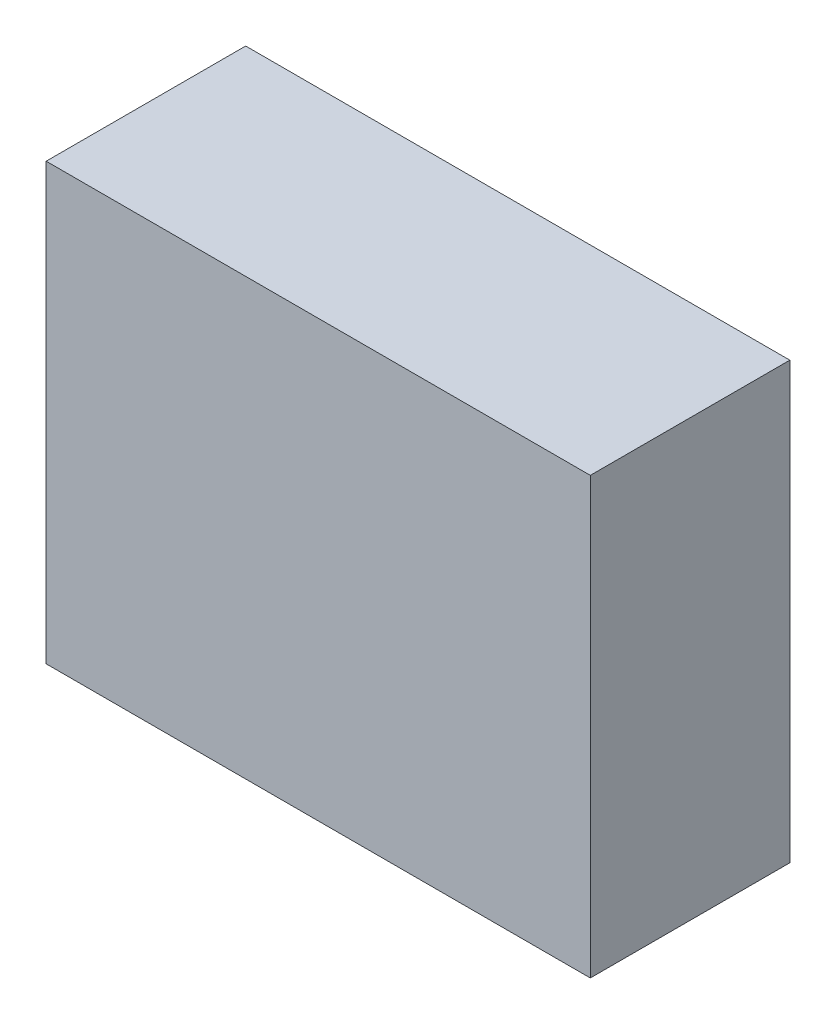
SolidWorks part; units mm, degrees
ref_plane "Front Plane" through (0, 0, 0) normal (0, 0, 1) x (1, 0, 0)
ref_plane "Top Plane" through (0, 0, 0) normal (0, 1, 0) x (1, 0, 0)
ref_plane "Right Plane" through (0, 0, 0) normal (1, 0, 0) x (0, 0, -1)
other "Configuration Table"
sketch "Sketch2" plane through (0, 0, 0) normal (0, 0, 1) x (1, 0, 0)
  line L1 (-15, -12) -> (15, -12)
  line L2 (-15, -12) -> (-15, 12)
  line L3 (-15, 12) -> (15, 12)
  line L4 (15, -12) -> (15, 12)
extrude "Reference_coupon" add sketch "Sketch2" along normal blind 11 from offset 0
